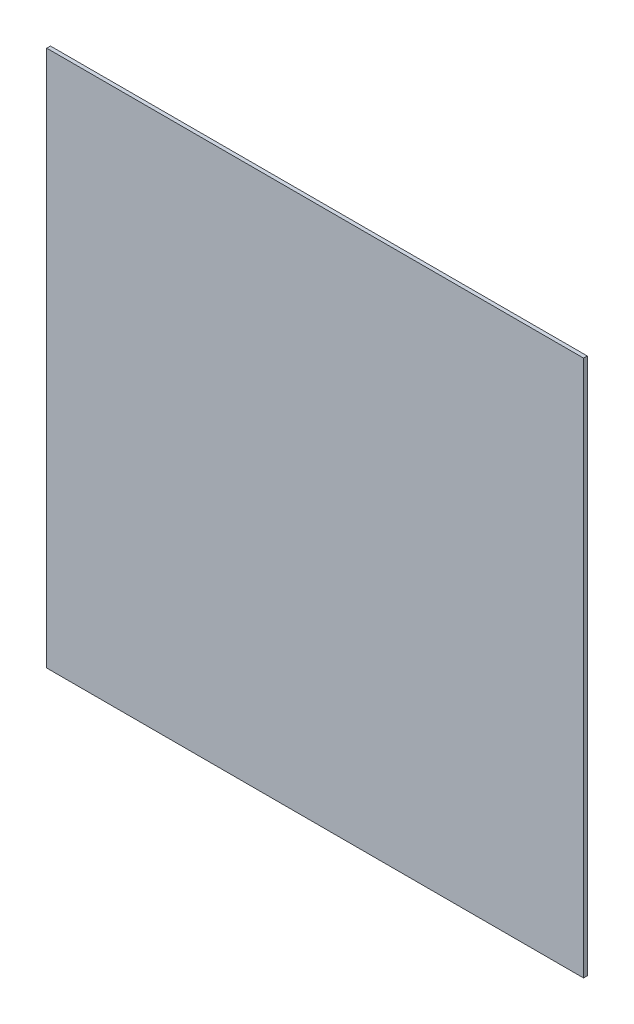
SolidWorks part; units mm, degrees
ref_plane "Front Plane" through (0, 0, 0) normal (0, 0, 1) x (1, 0, 0)
ref_plane "Top Plane" through (0, 0, 0) normal (0, 1, 0) x (1, 0, 0)
ref_plane "Right Plane" through (0, 0, 0) normal (1, 0, 0) x (0, 0, -1)
sketch "Sketch1" plane through (0, 0, 0) normal (0, 0, 1) x (1, 0, 0)
  line L1 (-228.6, -228.6) -> (228.6, -228.6)
  line L2 (-228.6, -228.6) -> (-228.6, 228.6)
  line L3 (-228.6, 228.6) -> (228.6, 228.6)
  line L4 (228.6, -228.6) -> (228.6, 228.6)
  line L5 (-228.6, -228.6) -> (228.6, 228.6) construction
  line L6 (-228.6, 228.6) -> (228.6, -228.6) construction
  point P0 (0, 0)
  dimension "D1" = 457.2
  dimension "D2" = 457.2
extrude "Boss-Extrude1" add sketch "Sketch1" along normal blind 3.175
